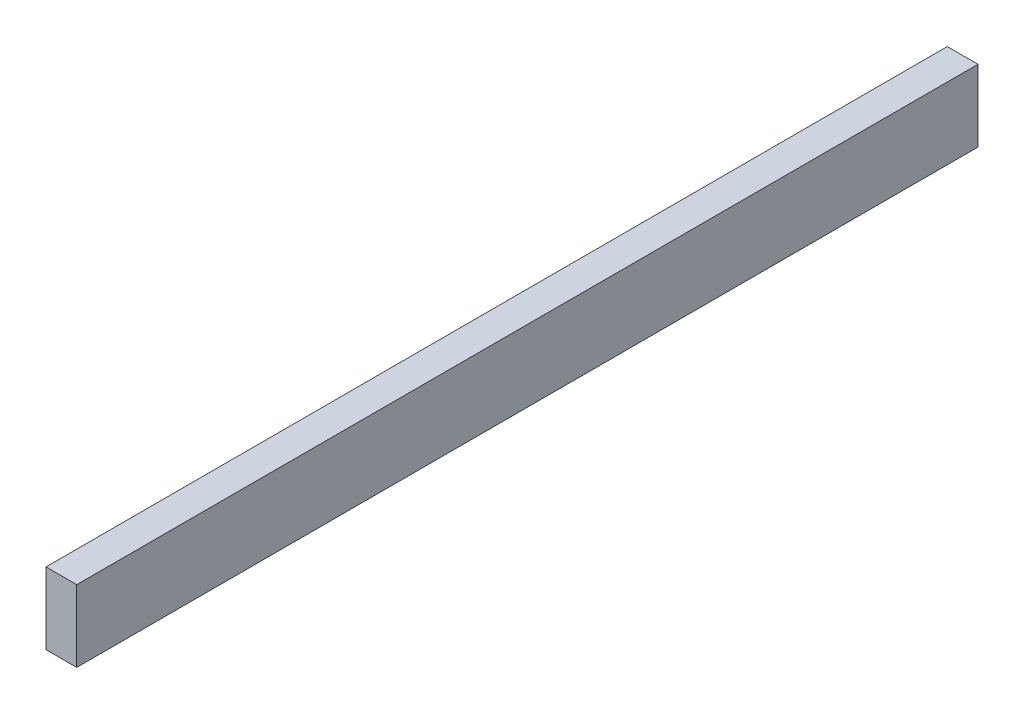
SolidWorks part; units mm, degrees
ref_plane "Front Plane" through (0, 0, 0) normal (0, 0, 1) x (1, 0, 0)
ref_plane "Top Plane" through (0, 0, 0) normal (0, 1, 0) x (1, 0, 0)
ref_plane "Right Plane" through (0, 0, 0) normal (1, 0, 0) x (0, 0, -1)
sketch "Sketch1" plane through (0, 0, 0) normal (1, 0, 0) x (0, 0, -1)
  line L1 (-558.8, -44.45) -> (558.8, -44.45)
  line L2 (-558.8, -44.45) -> (-558.8, 44.45)
  line L3 (-558.8, 44.45) -> (558.8, 44.45)
  line L4 (558.8, -44.45) -> (558.8, 44.45)
  line L5 (-558.8, -44.45) -> (558.8, 44.45) construction
  line L6 (-558.8, 44.45) -> (558.8, -44.45) construction
  point P0 (0, 0)
  dimension "D1" = 88.9
  dimension "D2" = 1117.6
extrude "Boss-Extrude1" add sketch "Sketch1" along normal blind 38.1
